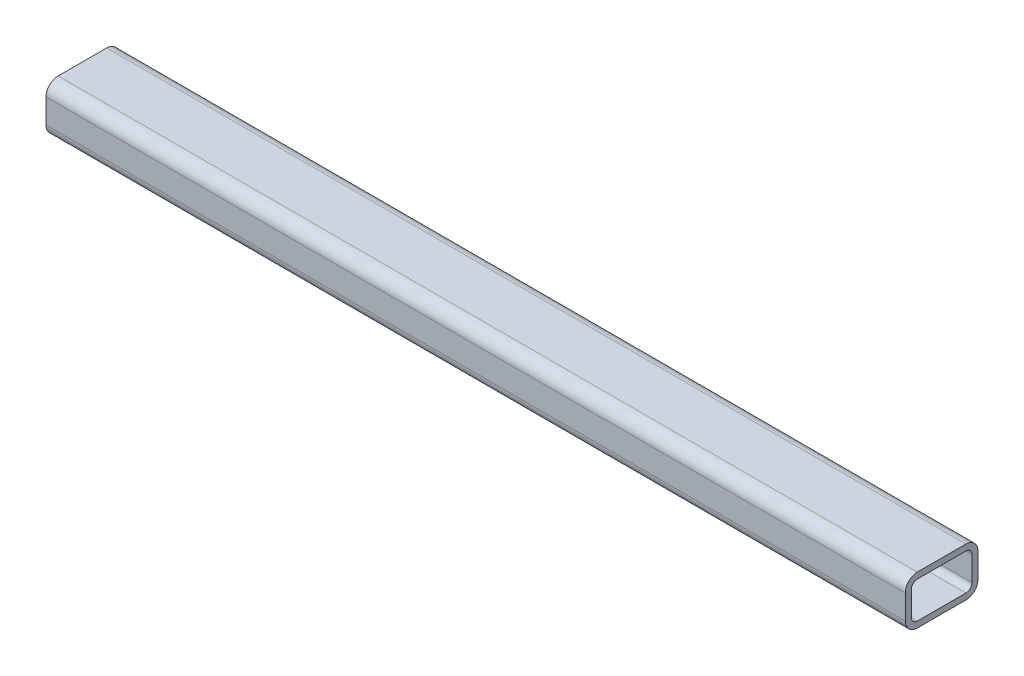
SolidWorks part; units mm, degrees
ref_plane "Alzado" through (0, 0, 0) normal (0, 0, 1) x (1, 0, 0)
ref_plane "Planta" through (0, 0, 0) normal (0, 1, 0) x (1, 0, 0)
ref_plane "Vista lateral" through (0, 0, 0) normal (1, 0, 0) x (0, 0, -1)
sketch "Croquis1" plane through (0, 0, 0) normal (0, 0, 1) x (1, 0, 0)
  line L0 (0, 0) -> (900, 0)
  dimension "D1" = 900
other "Tubo rectangular 3 X 2 X 0.25(1)"
ref_plane "Plano1" through (0, 0, 0) normal (1, 0, 0) x (0, 1, 0)
sketch "Sketch1" plane through (0, 0, 0) normal (1, 0, 0) x (0, 1, 0)
  line L0 (-12.7, -31.75) -> (12.7, -31.75)
  line L1 (-19.05, -25.4) -> (-19.05, 25.4)
  line L2 (12.7, 31.75) -> (-12.7, 31.75)
  line L3 (19.05, 25.4) -> (19.05, -25.4)
  line L4 (-12.7, -38.1) -> (12.7, -38.1)
  line L5 (-25.4, -25.4) -> (-25.4, 25.4)
  line L6 (12.7, 38.1) -> (-12.7, 38.1)
  line L7 (25.4, 25.4) -> (25.4, -25.4)
  line L8 (0, 0) -> (25.4, 0) construction
  line L9 (0, 0) -> (0, 38.1) construction
  arc A0 (25.4, 25.4) -> (12.7, 38.1) centre (12.7, 25.4) ccw
  arc A1 (12.7, -38.1) -> (25.4, -25.4) centre (12.7, -25.4) ccw
  arc A2 (-25.4, -25.4) -> (-12.7, -38.1) centre (-12.7, -25.4) ccw
  arc A3 (-12.7, 38.1) -> (-25.4, 25.4) centre (-12.7, 25.4) ccw
  arc A4 (-12.7, 31.75) -> (-19.05, 25.4) centre (-12.7, 25.4) ccw
  arc A5 (19.05, 25.4) -> (12.7, 31.75) centre (12.7, 25.4) ccw
  arc A6 (12.7, -31.75) -> (19.05, -25.4) centre (12.7, -25.4) ccw
  arc A7 (-19.05, -25.4) -> (-12.7, -31.75) centre (-12.7, -25.4) ccw
  point P3 (0, -38.1)
  point P4 (-25.4, 0)
  point P5 (0, 0)
  point P6 (25.4, -38.1)
  point P7 (-25.4, -38.1)
  point P8 (-25.4, 38.1)
  point P33 (0, 0)
  point P35 (25.4, 38.1)
  point P36 (25.4, 0)
  point P37 (0, 38.1)
  dimension "D1" = 12.7
  dimension "Thickness" = 6.35
  dimension "V_leg" = 76.2
  dimension "H_leg" = 50.8
